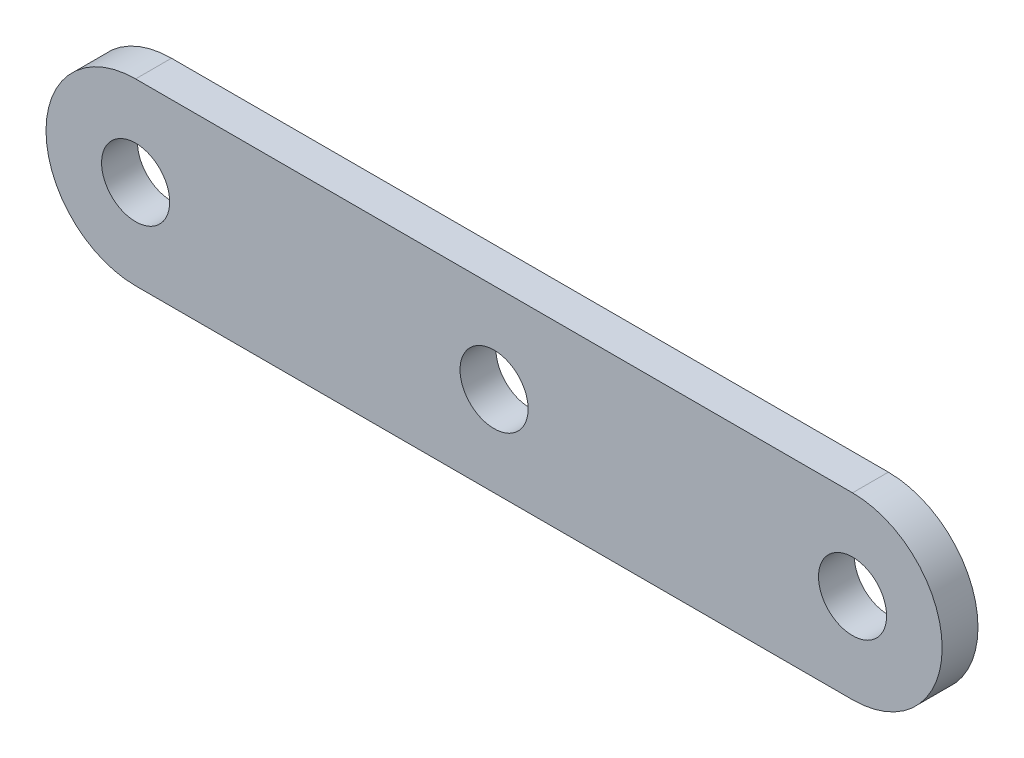
SolidWorks part; units mm, degrees
ref_plane "Front Plane" through (0, 0, 0) normal (0, 0, 1) x (1, 0, 0)
ref_plane "Top Plane" through (0, 0, 0) normal (0, 1, 0) x (1, 0, 0)
ref_plane "Right Plane" through (0, 0, 0) normal (1, 0, 0) x (0, 0, -1)
sketch "Croquis1" plane through (0, 0, 0) normal (0, 0, 1) x (1, 0, 0)
  line L1 (25.4, -6.35) -> (-25.4, -6.35)
  line L3 (25.4, 6.35) -> (-25.4, 6.35)
  line L5 (25.4, -6.35) -> (-25.4, 6.35) construction
  arc A0 (-25.4, 6.35) -> (-25.4, -6.35) centre (-25.4, 0) ccw
  arc A1 (25.4, -6.35) -> (25.4, 6.35) centre (25.4, 0) ccw
  point P0 (0, 0)
  dimension "D2" = 6.35
  dimension "D1" = 50.8
extrude "Saliente-Extruir1" add sketch "Croquis1" along normal mid plane 2.54
sketch "Croquis2" plane through (0, 0, 1.27) normal (0, 0, 1) x (1, 0, 0)
  circle A0 centre (-25.4, 0) radius 2.413
  dimension "D1" = 4.826
extrude "Cortar-Extruir1" cut sketch "Croquis2" against normal through all
pattern_linear "MatrizL1" count 3 spacing 25.4 along (1, 0, 0) of "Cortar-Extruir1"
